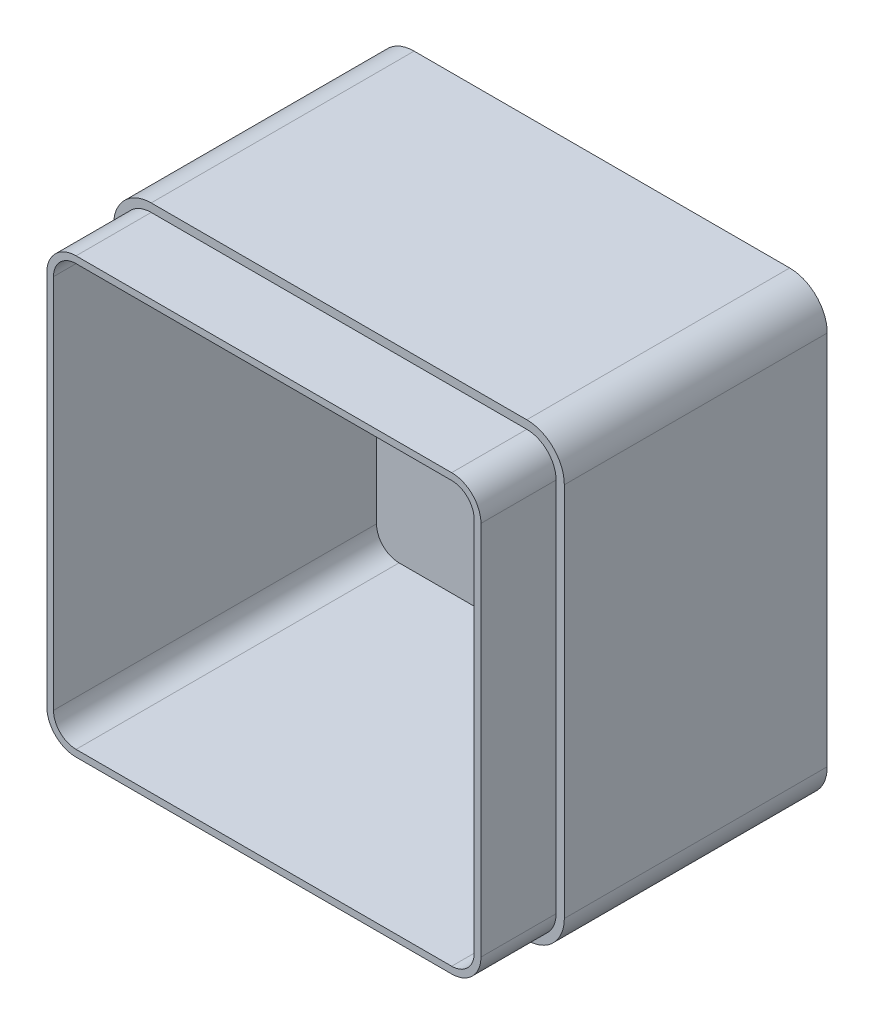
SolidWorks part; units mm, degrees
ref_plane "Front Plane" through (0, 0, 0) normal (0, 0, 1) x (1, 0, 0)
ref_plane "Top Plane" through (0, 0, 0) normal (0, 1, 0) x (1, 0, 0)
ref_plane "Right Plane" through (0, 0, 0) normal (1, 0, 0) x (0, 0, -1)
sketch "Sketch2" plane through (0, 0, 0) normal (0, 0, 1) x (1, 0, 0)
  line L1 (0, 0) -> (120, 0)
  line L2 (0, 0) -> (0, 120)
  line L3 (0, 120) -> (120, 120)
  line L4 (120, 0) -> (120, 120)
  dimension "D1" = 120
  dimension "D2" = 120
extrude "Boss-Extrude1" add sketch "Sketch2" along normal blind 90
fillet "Fillet1" radius 10 4 edges at (0, 0, 45) (120, 0, 45) (120, 120, 45) (0, 120, 45)
shell "Shell1" thickness 4
sketch "Sketch4" plane through (0, 0, 90) normal (0, 0, 1) x (1, 0, 0)
  line L0 (2.2, 110) -> (2.2, 10)
  line L1 (10, 2.2) -> (110, 2.2)
  line L2 (117.8, 10) -> (117.8, 110)
  line L3 (110, 117.8) -> (10, 117.8)
  line L4 (0, 110) -> (0, 10)
  line L5 (10, 0) -> (110, 0)
  line L6 (120, 10) -> (120, 110)
  line L7 (110, 120) -> (10, 120)
  line L8 (0, 110) -> (0, 10)
  line L9 (10, 0) -> (110, 0)
  line L10 (120, 10) -> (120, 110)
  line L11 (110, 120) -> (10, 120)
  arc A0 (2.2, 10) -> (10, 2.2) centre (10, 10) ccw
  arc A1 (110, 2.2) -> (117.8, 10) centre (110, 10) ccw
  arc A2 (117.8, 110) -> (110, 117.8) centre (110, 110) ccw
  arc A3 (10, 117.8) -> (2.2, 110) centre (10, 110) ccw
  arc A4 (0, 10) -> (10, 0) centre (10, 10) ccw
  arc A5 (110, 0) -> (120, 10) centre (110, 10) ccw
  arc A6 (120, 110) -> (110, 120) centre (110, 110) ccw
  arc A7 (10, 120) -> (0, 110) centre (10, 110) ccw
  arc A8 (0, 10) -> (10, 0) centre (10, 10) ccw
  arc A9 (110, 0) -> (120, 10) centre (110, 10) ccw
  arc A10 (120, 110) -> (110, 120) centre (110, 110) ccw
  arc A11 (10, 120) -> (0, 110) centre (10, 110) ccw
  dimension "D1" = 0
  dimension "D2" = 2.2
extrude "Cut-Extrude1" cut sketch "Sketch4" against normal blind 20
equation "\"PrintFitAllowance\"= 0.2mm"
equation "\"D2@Sketch4\"=\"PrintFitAllowance\" + 2.00mm"
